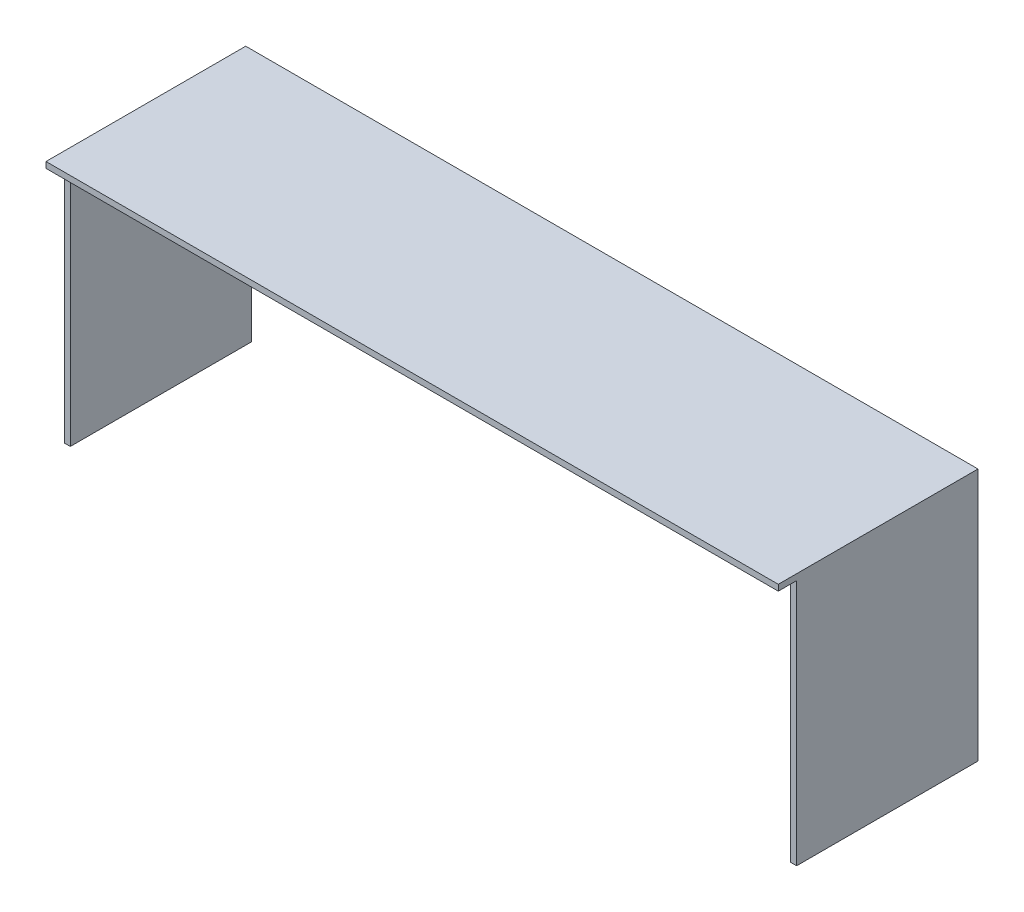
SolidWorks part; units mm, degrees
ref_plane "Front Plane" through (0, 0, 0) normal (0, 0, 1) x (1, 0, 0)
ref_plane "Top Plane" through (0, 0, 0) normal (0, 1, 0) x (1, 0, 0)
ref_plane "Right Plane" through (0, 0, 0) normal (1, 0, 0) x (0, 0, -1)
sketch "Sketch1" plane through (0, 0, 0) normal (0, 1, 0) x (1, 0, 0)
  line L1 (-1100, -300) -> (1100, -300)
  line L2 (-1100, -300) -> (-1100, 300)
  line L3 (-1100, 300) -> (1100, 300)
  line L4 (1100, -300) -> (1100, 300)
  line L5 (-1100, -300) -> (1100, 300) construction
  line L6 (-1100, 300) -> (1100, -300) construction
  point P0 (0, 0)
  dimension "D1" = 2200
  dimension "D2" = 600
extrude "Boss-Extrude1" add sketch "Sketch1" along normal blind 18
sketch "Sketch2" plane through (0, 0, 0) normal (0, -1, 0) x (1, 0, 0)
  line L1 (-1100, -300) -> (-1082, -300)
  line L2 (-1100, -300) -> (-1100, 245)
  line L3 (-1100, 245) -> (-1082, 245)
  line L4 (-1082, -300) -> (-1082, 245)
  dimension "D1" = 18
  dimension "D2" = 545
extrude "Boss-Extrude2" add sketch "Sketch2" along normal blind 742
mirror "Mirror1" about plane through (0, 0, 0) normal (1, 0, 0) of "Boss-Extrude2"
sketch "Sketch3" plane through (-1082, 0, 0) normal (1, 0, 0) x (0, 0, -1)
  line L0 (300, 0) -> (-245, 0) construction
  line L1 (253, 0) -> (235, 0)
  line L2 (253, 0) -> (253, -280)
  line L3 (253, -280) -> (235, -280)
  line L4 (235, 0) -> (235, -280)
  line L5 (-245, -742) -> (-245, 0) construction
  dimension "D1" = 18
  dimension "D2" = 480
  dimension "D3" = 280
extrude "Boss-Extrude3" add sketch "Sketch3" along normal up to surface (2164 mm away) up to face at (1082, -371, -27.5)
